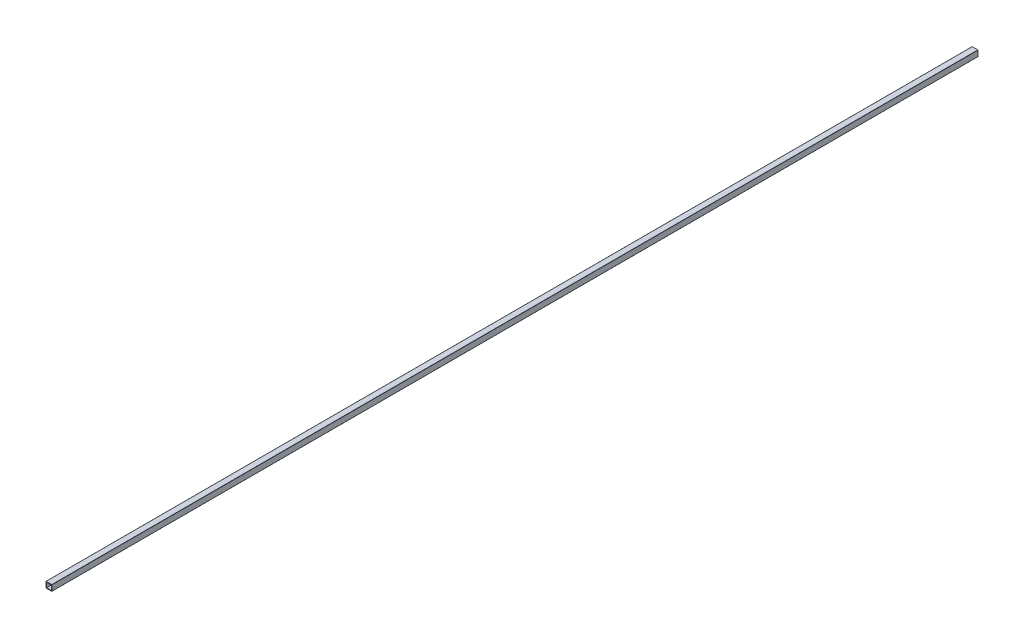
SolidWorks part; units mm, degrees
material "AISI 1035 Acero (SS)"
ref_plane "Alzado" through (0, 0, 0) normal (0, 0, 1) x (1, 0, 0)
ref_plane "Planta" through (0, 0, 0) normal (0, 1, 0) x (1, 0, 0)
ref_plane "Vista lateral" through (0, 0, 0) normal (1, 0, 0) x (0, 0, -1)
sketch "Croquis1" plane through (0, 0, 0) normal (0, 0, 1) x (1, 0, 0)
  line L1 (-18.05, -19.05) -> (18.05, -19.05)
  line L2 (-19.05, -18.05) -> (-19.05, 18.05)
  line L3 (-18.05, 19.05) -> (18.05, 19.05)
  line L4 (19.05, -18.05) -> (19.05, 18.05)
  line L5 (-19.05, -19.05) -> (19.05, 19.05) construction
  line L6 (-19.05, 19.05) -> (19.05, -19.05) construction
  line L10 (-15.25, -15.25) -> (-15.25, 15.25)
  line L11 (-15.25, 15.25) -> (15.25, 15.25)
  line L12 (15.25, -15.25) -> (15.25, 15.25)
  line L13 (-15.25, -15.25) -> (15.25, -15.25)
  arc A0 (18.05, 19.05) -> (19.05, 18.05) centre (18.05, 18.05) cw
  arc A1 (18.05, -19.05) -> (19.05, -18.05) centre (18.05, -18.05) ccw
  arc A2 (-18.05, -19.05) -> (-19.05, -18.05) centre (-18.05, -18.05) cw
  arc A3 (-19.05, 18.05) -> (-18.05, 19.05) centre (-18.05, 18.05) cw
  arc A4 (-15.25, 15.25) -> (-15.25, 15.25) centre (-15.25, 15.25) cw
  arc A5 (15.25, 15.25) -> (15.25, 15.25) centre (15.25, 15.25) cw
  arc A6 (15.25, -15.25) -> (15.25, -15.25) centre (15.25, -15.25) ccw
  arc A7 (-15.25, -15.25) -> (-15.25, -15.25) centre (-15.25, -15.25) cw
  point P0 (0, 0)
  dimension "D2" = 1
  dimension "D1" = 38.1
  dimension "D3" = 3.8
extrude "Saliente-Extruir1" add sketch "Croquis1" along normal blind 6000
